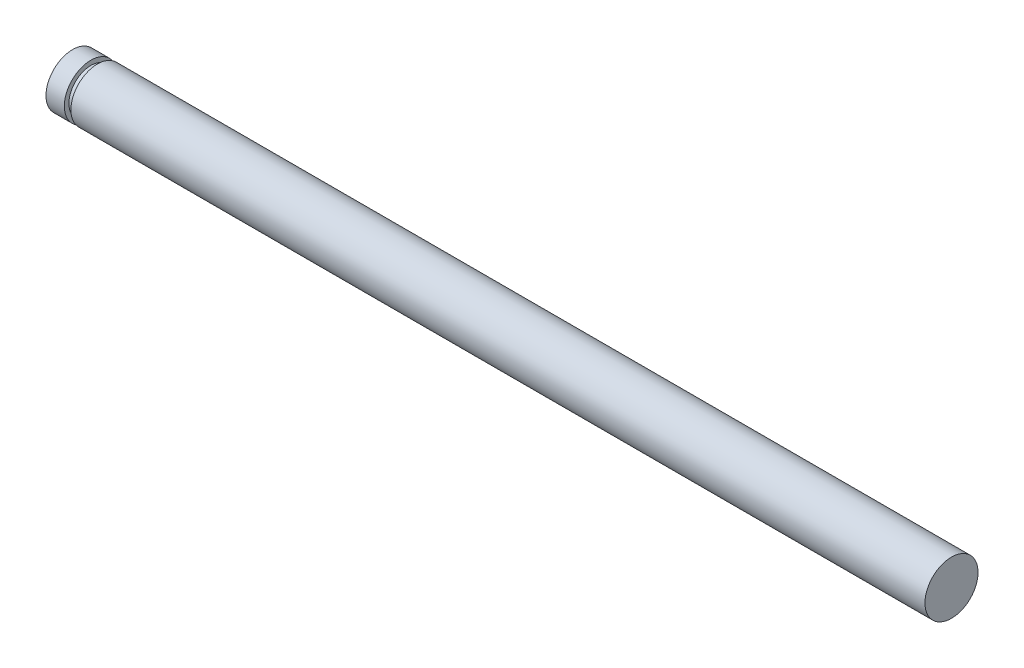
SolidWorks part; units mm, degrees
ref_plane "Front Plane" through (0, 0, 0) normal (0, 0, 1) x (1, 0, 0)
ref_plane "Top Plane" through (0, 0, 0) normal (0, 1, 0) x (1, 0, 0)
ref_plane "Right Plane" through (0, 0, 0) normal (1, 0, 0) x (0, 0, -1)
sketch "Sketch1" plane through (0, 0, 0) normal (0, 0, 1) x (1, 0, 0)
  line L0 (-12.1989, 0) -> (11.8011, 0) construction
  line L1 (-12.1989, 0) -> (-12.1989, 0.725)
  line L2 (-12.1989, 0.725) -> (-11.6989, 0.725)
  line L3 (-11.6989, 0.725) -> (-11.6989, 0.6)
  line L4 (-11.6989, 0.6) -> (-11.5189, 0.6)
  line L5 (-11.5189, 0.6) -> (-11.5189, 0.725)
  line L6 (-11.5189, 0.725) -> (11.8011, 0.725)
  line L7 (11.8011, 0.725) -> (11.8011, 0)
  line L8 (-12.1989, 0) -> (11.8011, 0)
  point P3 (0, 0)
  point P10 (0, 0)
  point P11 (0, 0)
  point P12 (0, 0)
  dimension "D1" = 24
  dimension "D2" = 1.45
  dimension "D3" = 0.5
  dimension "D4" = 0.18
  dimension "D5" = 1.2
revolve "Revolve1" add sketch "Sketch1" angle 360 about L0
